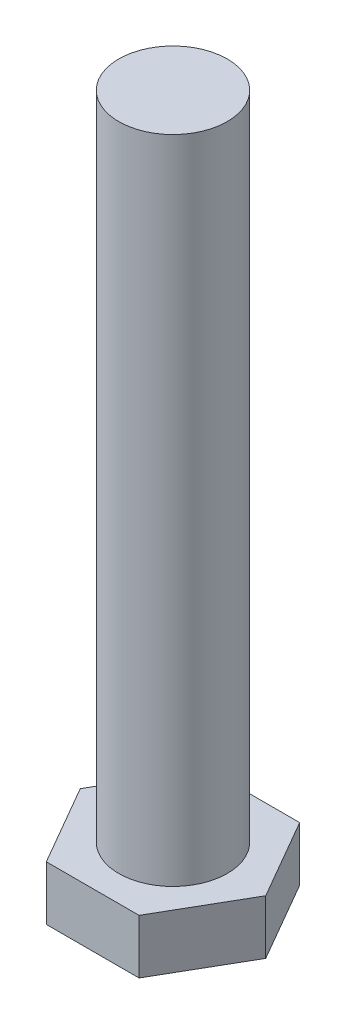
SolidWorks part; units mm, degrees
ref_plane "Front Plane" through (0, 0, 0) normal (0, 0, 1) x (1, 0, 0)
ref_plane "Top Plane" through (0, 0, 0) normal (0, 1, 0) x (1, 0, 0)
ref_plane "Right Plane" through (0, 0, 0) normal (1, 0, 0) x (0, 0, -1)
sketch "Sketch1" plane through (0, 0, 0) normal (0, 1, 0) x (1, 0, 0)
  line L1 (5.4259, -9.398) -> (10.8519, 0)
  line L2 (10.8519, 0) -> (5.4259, 9.398)
  line L3 (5.4259, 9.398) -> (-5.4259, 9.398)
  line L4 (-5.4259, 9.398) -> (-10.8519, 0)
  line L5 (-10.8519, 0) -> (-5.4259, -9.398)
  line L6 (-5.4259, -9.398) -> (5.4259, -9.398)
  circle A0 centre (0, 0) radius 9.398 construction
  dimension "D1" = 18.796
extrude "Boss-Extrude1" add sketch "Sketch1" along normal blind 6.35
sketch "Sketch2" plane through (0, 6.35, 0) normal (0, 1, 0) x (1, 0, 0)
  circle A0 centre (0, 0) radius 6.35
  dimension "D1" = 12.7
extrude "Boss-Extrude2" add sketch "Sketch2" along normal blind 76.2
